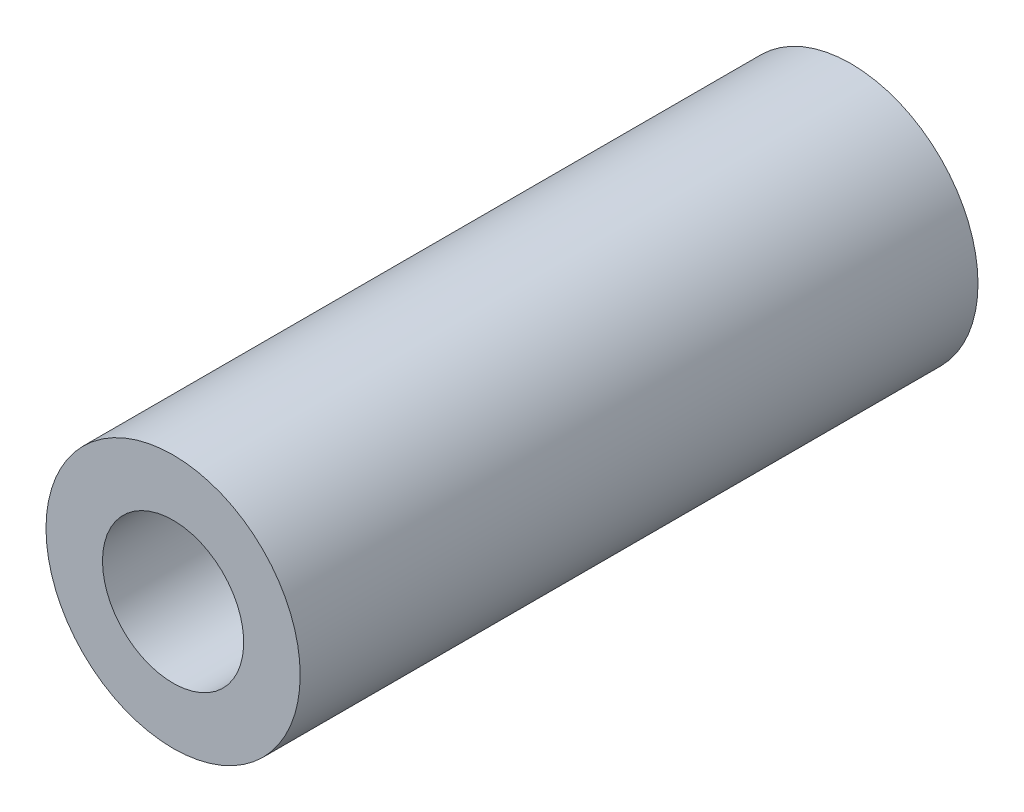
SolidWorks part; units mm, degrees
ref_plane "Front Plane" through (0, 0, 0) normal (0, 0, 1) x (1, 0, 0)
ref_plane "Top Plane" through (0, 0, 0) normal (0, 1, 0) x (1, 0, 0)
ref_plane "Right Plane" through (0, 0, 0) normal (1, 0, 0) x (0, 0, -1)
sketch "Sketch1" plane through (0, 0, 0) normal (0, 0, 1) x (1, 0, 0)
  line L0 (-28.575, 0) -> (28.575, 0) construction
  line L1 (0, -28.575) -> (0, 28.575) construction
  circle A0 centre (0, 0) radius 28.575
  circle A1 centre (0, 0) radius 15.875
  point P4 (0, 0)
  point P9 (0, 0)
  point P10 (15.875, 0)
  dimension "D1" = 31.75
  dimension "OD" = 57.15
  dimension "Wall Thickness" = 12.7
sketch "Sketch2" plane through (0, 0, 0) normal (1, 0, 0) x (0, 0, -1)
  line L0 (76.2, 28.575) -> (-76.2, 28.575) construction
  line L1 (0, 28.575) -> (0, -28.575) construction
  point P3 (-47.625, 28.575)
  point P4 (0, 28.575)
  point P5 (47.625, 28.575)
  dimension "D1" = 28.575
  dimension "D2" = 28.575
  dimension "Length" = 152.4
sketch "Sketch3" plane through (0, 0, 0) normal (0, 0, 1) x (1, 0, 0)
  line L0 (0, -28.575) -> (0, 28.575) construction
  circle A0 centre (0, 0) radius 28.575
  circle A1 centre (0, 0) radius 15.875
  circle A2 centre (0, 0) radius 15.875 construction
extrude "Boss-Extrude1" add sketch "Sketch3" along normal mid plane 152.4
equation "\"D1@Boss-Extrude1\" = \"Length@Sketch2\""
equation "\"D1@Sketch2\"=\"OD@Sketch1\"*.5"
equation "\"D2@Sketch2\"=\"D1@Sketch2\""
